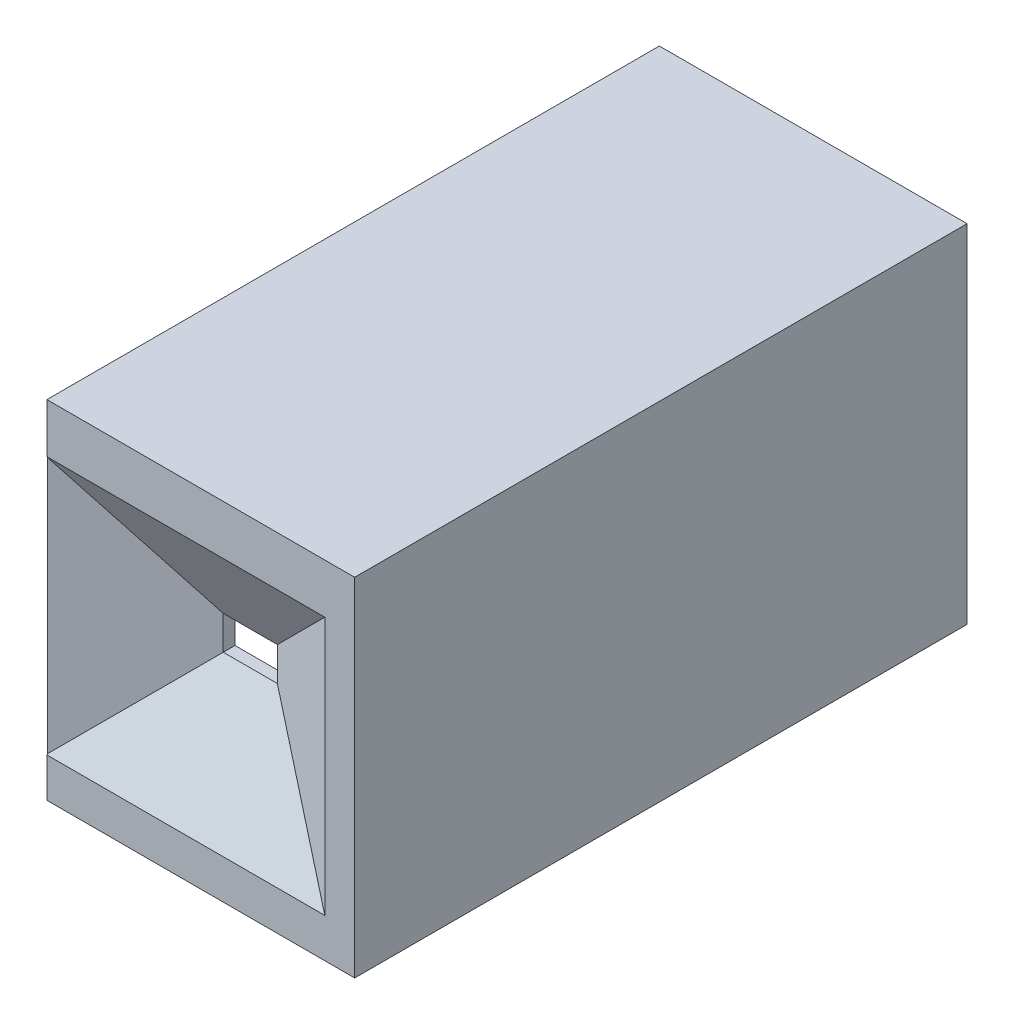
SolidWorks part; units mm, degrees
ref_plane "Front Plane" through (0, 0, 0) normal (0, 0, 1) x (1, 0, 0)
ref_plane "Top Plane" through (0, 0, 0) normal (0, 1, 0) x (1, 0, 0)
ref_plane "Right Plane" through (0, 0, 0) normal (1, 0, 0) x (0, 0, -1)
sketch "Sketch1" plane through (0, 0, 0) normal (0, 0, 1) x (1, 0, 0)
  line L10 (0, 0) -> (13.075, 0)
  line L15 (-13.575, -13.5) -> (-13.575, 13.5)
  line L16 (-13.575, 13.5) -> (13.575, 13.5)
  line L21 (13.575, -13.5) -> (13.575, 13.5)
  line L22 (-13.575, -13.5) -> (13.575, -13.5)
  line L28 (-12.425, -3.5) -> (-12.425, 3.5)
  line L29 (-12.425, 3.5) -> (-7.125, 3.5)
  line L30 (-7.125, -3.5) -> (-7.125, 3.5)
  line L31 (-12.425, -3.5) -> (-7.125, -3.5)
  line L32 (12.425, -3.5) -> (7.125, -3.5)
  line L33 (7.125, -3.5) -> (7.125, 3.5)
  line L34 (12.425, -3.5) -> (12.425, 3.5)
  line L35 (12.425, 3.5) -> (7.125, 3.5)
  line L36 (-2.65, -1.65) -> (-2.65, 1.65)
  line L37 (-2.65, 1.65) -> (2.65, 1.65)
  line L38 (2.65, -1.65) -> (2.65, 1.65)
  line L39 (-2.65, -1.65) -> (2.65, -1.65)
  circle A5 centre (10.325, 10.25) radius 1.175
  circle A6 centre (10.325, -10.25) radius 1.175
  circle A7 centre (-10.325, -10.25) radius 1.175
  circle A8 centre (-10.325, 10.25) radius 1.175
  point P0 (0, 0)
  point P16 (0, 0)
  point P31 (-9.775, 0)
  dimension "D10" = 2.35
  dimension "D11" = 2.35
  dimension "D12" = 2.35
  dimension "D13" = 2.35
  dimension "D18" = 13.075
ref_plane "Plane1" through (0, 0, 0) normal (0, 0, 1) x (1, 0, 0)
sketch "Sketch2" plane through (0, 0, 0) normal (0, 0, 1) x (1, 0, 0)
  line L0 (-16.575, 16.5) -> (-16.575, -16.5)
  line L5 (-16.575, -16.5) -> (16.575, -16.5)
  line L6 (16.575, 16.5) -> (16.575, -16.5)
  line L7 (-16.575, 16.5) -> (16.575, 16.5)
extrude "Boss-Extrude1" add sketch "Sketch2" along normal blind 7.5
ref_plane "Plane2" through (0, 0, 0) normal (0, 0, 1) x (1, 0, 0)
sketch "Sketch3" plane through (0, 0, 0) normal (0, 0, 1) x (1, 0, 0)
  circle A0 centre (10.325, 10.25) radius 1.175
  circle A1 centre (-10.325, 10.25) radius 1.175
  circle A2 centre (10.325, -10.25) radius 1.175
  circle A3 centre (-10.325, -10.25) radius 1.175
extrude "Cut-Extrude1" cut sketch "Sketch3" along normal blind 4.5
ref_plane "Plane3" through (0, 0, 0) normal (0, 0, 1) x (1, 0, 0)
sketch "Sketch4" plane through (0, 0, 0) normal (0, 0, 1) x (1, 0, 0)
  line L1 (12.425, -3.5) -> (7.125, -3.5)
  line L2 (12.425, -3.5) -> (12.425, 3.5)
  line L3 (12.425, 3.5) -> (7.125, 3.5)
  line L4 (7.125, -3.5) -> (7.125, 3.5)
  line L5 (-7.125, -3.5) -> (-12.425, -3.5)
  line L6 (-7.125, -3.5) -> (-7.125, 3.5)
  line L7 (-7.125, 3.5) -> (-12.425, 3.5)
  line L8 (-12.425, -3.5) -> (-12.425, 3.5)
extrude "Cut-Extrude2" cut sketch "Sketch4" along normal blind 3.4
ref_plane "Plane4" through (0, 0, 0) normal (0, 0, 1) x (1, 0, 0)
sketch "Sketch5" plane through (0, 0, 0) normal (0, 0, 1) x (1, 0, 0)
  line L1 (8.5467, -12.7134) -> (-8.766, -12.7134)
  line L2 (8.5467, -12.7134) -> (8.5467, -10.9049)
  line L3 (8.5467, -10.9049) -> (-8.766, -10.9049)
  line L4 (-8.766, -12.7134) -> (-8.766, -10.9049)
extrude "Cut-Extrude3" cut sketch "Sketch5" along normal blind 2
ref_plane "Plane5" through (0, 0, 0) normal (0, 0, 1) x (1, 0, 0)
sketch "Sketch6" plane through (0, 0, 0) normal (0, 0, 1) x (1, 0, 0)
  line L1 (2.65, -1.65) -> (-2.65, -1.65)
  line L2 (2.65, -1.65) -> (2.65, 1.65)
  line L3 (2.65, 1.65) -> (-2.65, 1.65)
  line L4 (-2.65, -1.65) -> (-2.65, 1.65)
extrude "Cut-Extrude4" cut sketch "Sketch6" along normal through all
chamfer "Chamfer3" distance 11 angle 30 4 edges at (-2.65, 0, 7.5) (0, -1.65, 7.5) (2.65, 0, 7.5) (0, 1.65, 7.5)
ref_plane "Plane7" through (0, 0, 0) normal (0, 0, 1) x (1, 0, 0)
sketch "Sketch7" plane through (0, 0, 0) normal (0, 0, 1) x (1, 0, 0)
  line L0 (16.575, 16.5) -> (-16.575, 16.5) construction
  line L1 (16.575, -16.5) -> (13.575, -16.5)
  line L2 (16.575, -16.5) -> (16.575, 16.5)
  line L3 (16.575, 16.5) -> (13.575, 16.5)
  line L4 (13.575, -16.5) -> (13.575, 16.5)
  line L6 (13.575, 13.5) -> (-16.575, 13.5)
  line L7 (13.575, 13.5) -> (13.575, 16.5)
  line L8 (13.575, 16.5) -> (-16.575, 16.5)
  line L9 (-16.575, 13.5) -> (-16.575, 16.5)
  line L10 (-13.575, 13.5) -> (-16.575, 13.5)
  line L11 (-13.575, 13.5) -> (-13.575, -16.5)
  line L12 (-13.575, -16.5) -> (-16.575, -16.5)
  line L13 (-16.575, 13.5) -> (-16.575, -16.5)
  dimension "D1" = 3
extrude "Boss-Extrude2" add sketch "Sketch7" against normal blind 52.5 contours L4 L1 L2 L3 | L9 L6 L4 L8 | L6 L13 L12 L11
sketch "Sketch8" plane through (0, 16.5, 0) normal (0, 1, 0) x (1, 0, 0)
  line L1 (-16.575, -7.5) -> (16.575, -7.5)
  line L2 (-16.575, -7.5) -> (-16.575, 52.5)
  line L3 (-16.575, 52.5) -> (16.575, 52.5)
  line L4 (16.575, -7.5) -> (16.575, 52.5)
extrude "Boss-Extrude3" add sketch "Sketch8" along normal blind 1
sketch "Sketch9" plane through (0, 0, -52.5) normal (0, 0, -1) x (-1, 0, 0)
  line L1 (13.575, -16.5) -> (16.575, -16.5)
  line L2 (13.575, -16.5) -> (13.575, 17.5)
  line L3 (13.575, 17.5) -> (16.575, 17.5)
  line L4 (16.575, -16.5) -> (16.575, 17.5)
extrude "Cut-Extrude5" cut sketch "Sketch9" against normal up to surface (60 mm away) up to face at (0, 0, 7.5)
sketch "Sketch10" plane through (-13.575, 0, 0) normal (-1, 0, 0) x (0, 0, 1)
  line L0 (7.5, 17.5) -> (-52.5, 17.5) construction
  line L1 (-52.5, 17.5) -> (-52.5, 13.5) construction
  line L2 (-22.5, 17.5) -> (-22.5, -16.5) construction
  line L3 (-52.5, -16.5) -> (0, -16.5) construction
  line L4 (-22.5, 0.5) -> (-9.591, 0.5) construction
  circle A0 centre (-50, 15.5) radius 0.75
  circle A1 centre (5, 15.5) radius 0.75
  circle A2 centre (5, -14.5) radius 0.75
  dimension "D2" = 1.5
  dimension "D1" = 2
  dimension "D3" = 2.5
extrude "Cut-Extrude6" cut sketch "Sketch10" against normal blind 2
sketch "Sketch11" plane through (0, -16.5, 0) normal (0, -1, 0) x (-1, 0, 0)
  line L0 (-16.575, -7.5) -> (-16.575, 52.5) construction
  line L1 (-16.575, 52.5) -> (-13.575, 52.5) construction
  line L2 (-16.575, 22.5) -> (5.2939, 22.5) construction
  circle A0 centre (-15.075, 49.5) radius 0.8
  circle A1 centre (-15.075, -4.5) radius 0.8
  circle A2 centre (12.075, -4.5) radius 0.8
  dimension "D1" = 1.6
  dimension "D2" = 1.5
  dimension "D3" = 3
extrude "Cut-Extrude7" cut sketch "Sketch11" against normal blind 2
sketch "Sketch12" plane through (0, 0, -52.5) normal (0, 0, -1) x (-1, 0, 0)
  line L0 (-16.575, 17.5) -> (13.575, 17.5) construction
  line L1 (-16.575, -16.5) -> (-16.575, 17.5) construction
  line L2 (-16.575, -16.5) -> (-13.575, -16.5) construction
  circle A0 centre (-14.575, 15.5) radius 0.8
  circle A1 centre (-15.075, -14.5) radius 0.8
  dimension "D3" = 1.6
  dimension "D6" = 1.6
  dimension "D1" = 2
  dimension "D2" = 2
  dimension "D4" = 2
  dimension "D5" = 1.5
extrude "Cut-Extrude9" cut sketch "Sketch12" against normal blind 5.8
